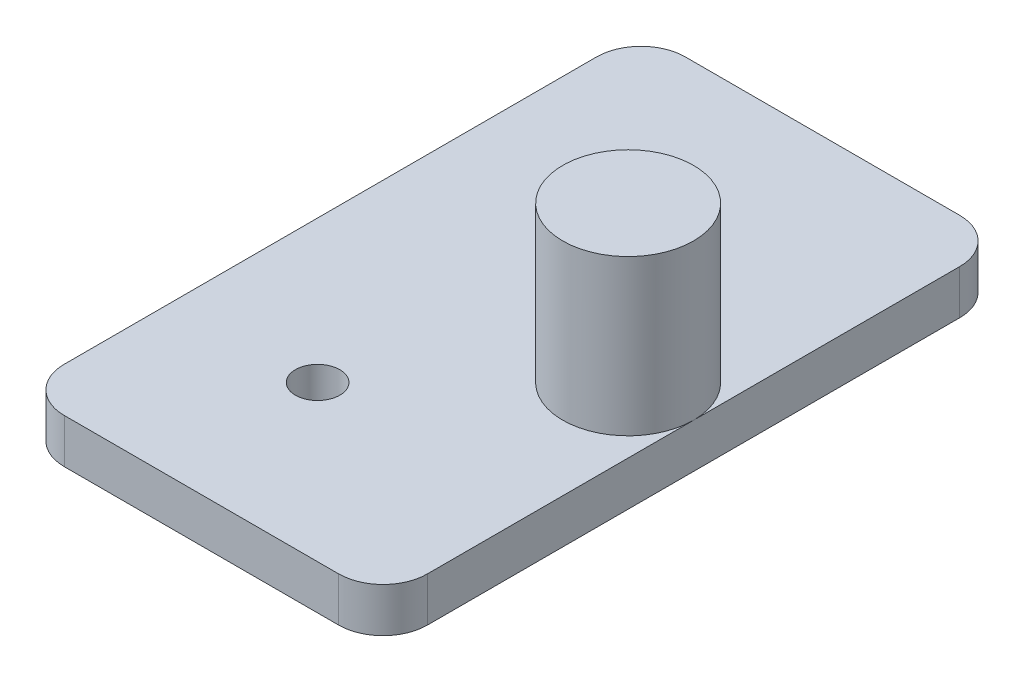
SolidWorks part; units mm, degrees
ref_plane "前视基准面" through (0, 0, 0) normal (0, 0, 1) x (1, 0, 0)
ref_plane "上视基准面" through (0, 0, 0) normal (0, 1, 0) x (1, 0, 0)
ref_plane "右视基准面" through (0, 0, 0) normal (1, 0, 0) x (0, 0, -1)
other "Configuration Table"
sketch "草图1" plane through (0, 0, 0) normal (0, 1, 0) x (1, 0, 0)
  line L0 (-20, 0) -> (20, 0) construction
  line L1 (-20, 14) -> (20, 14) construction
  line L2 (-20, 14) -> (-20, -14) construction
  line L3 (-20, -14) -> (20, -14) construction
  line L4 (20, 14) -> (20, -14) construction
  line L5 (-20, 14) -> (20, -14) construction
  line L6 (-20, -14) -> (20, 14) construction
  line L8 (4.0783, 14) -> (20, 14)
  line L9 (4.0783, 14) -> (4.0783, -14)
  line L10 (4.0783, -14) -> (20, -14)
  line L11 (20, 14) -> (20, -14) construction
  line L12 (20, 14) -> (20.45, 14)
  line L13 (20, 14) -> (20, -14) construction
  line L14 (20, -14) -> (20.45, -14)
  line L15 (20.45, 14) -> (20.45, -14)
  circle A0 centre (17.5, 0) radius 1
  circle A1 centre (17.5, 0) radius 2.95
  circle A2 centre (10.5, 7) radius 1
  circle A3 centre (10.5, -7) radius 1
  point P0 (0, 0)
  dimension "D3" = 2
  dimension "D4" = 5.9
  dimension "D7" = 2
  dimension "D1" = 40
  dimension "D2" = 28
  dimension "D6" = 2.5
  dimension "D8" = 7
  dimension "D9" = 9.5
extrude "凸台-拉伸1" add sketch "草图1" along normal blind 9 contours A1
sketch "草图2" plane through (0, 0, 0) normal (0, 1, 0) x (1, 0, 0)
  line L4 (4.0783, 14) -> (4.0783, -14)
  line L5 (4.0783, -14) -> (20, -14)
  line L6 (20, -14) -> (20.45, -14)
  line L7 (20, 14) -> (4.0783, 14)
  line L8 (4.0783, 14) -> (4.0783, -14)
  line L9 (4.0783, -14) -> (20, -14)
  line L11 (20, 14) -> (4.0783, 14)
  line L14 (20, -14) -> (20.45, -14)
  line L15 (20.45, -14) -> (20.45, 14)
  line L16 (20.45, -14) -> (20.45, 14)
  line L17 (20.45, 14) -> (20, 14)
  line L18 (20.45, 14) -> (20, 14)
  circle A1 centre (10.5, -7) radius 1
  circle A2 centre (10.5, -7) radius 1
  circle A3 centre (10.5, 7) radius 1
  circle A4 centre (10.5, 7) radius 1
  dimension "D1" = 0
  dimension "D2" = 0
  dimension "D5" = 0
extrude "凸台-拉伸2" add sketch "草图2" along normal blind 2
fillet "圆角1" radius 2 4 edges at (20.45, 1, 14) (4.0783, 1, 14) (4.0783, 1, -14) (20.45, 1, -14)
